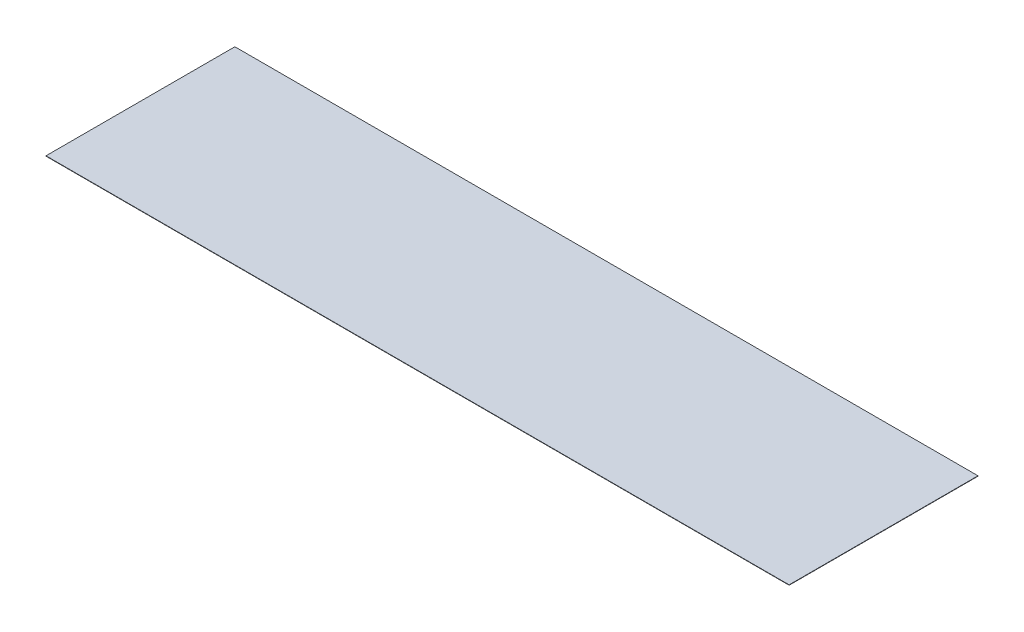
SolidWorks part; units mm, degrees
material "Silicon"
ref_plane "Front Plane" through (0, 0, 0) normal (0, 0, 1) x (1, 0, 0)
ref_plane "Top Plane" through (0, 0, 0) normal (0, 1, 0) x (1, 0, 0)
ref_plane "Right Plane" through (0, 0, 0) normal (1, 0, 0) x (0, 0, -1)
sketch "Sketch1" plane through (0, 0, 0) normal (0, 1, 0) x (1, 0, 0)
  line L1 (162.5, -41.3) -> (-162.5, -41.3)
  line L2 (162.5, -41.3) -> (162.5, 41.3)
  line L3 (162.5, 41.3) -> (-162.5, 41.3)
  line L4 (-162.5, -41.3) -> (-162.5, 41.3)
  line L5 (162.5, -41.3) -> (-162.5, 41.3) construction
  line L6 (162.5, 41.3) -> (-162.5, -41.3) construction
  point P0 (0, 0)
  dimension "D1" = 82.6
  dimension "D2" = 325
extrude "Boss-Extrude1" add sketch "Sketch1" along normal blind 0.16
ref_plane "Plane1" through (0, 0, 0) normal (0, 0, 1) x (1, 0, 0)
